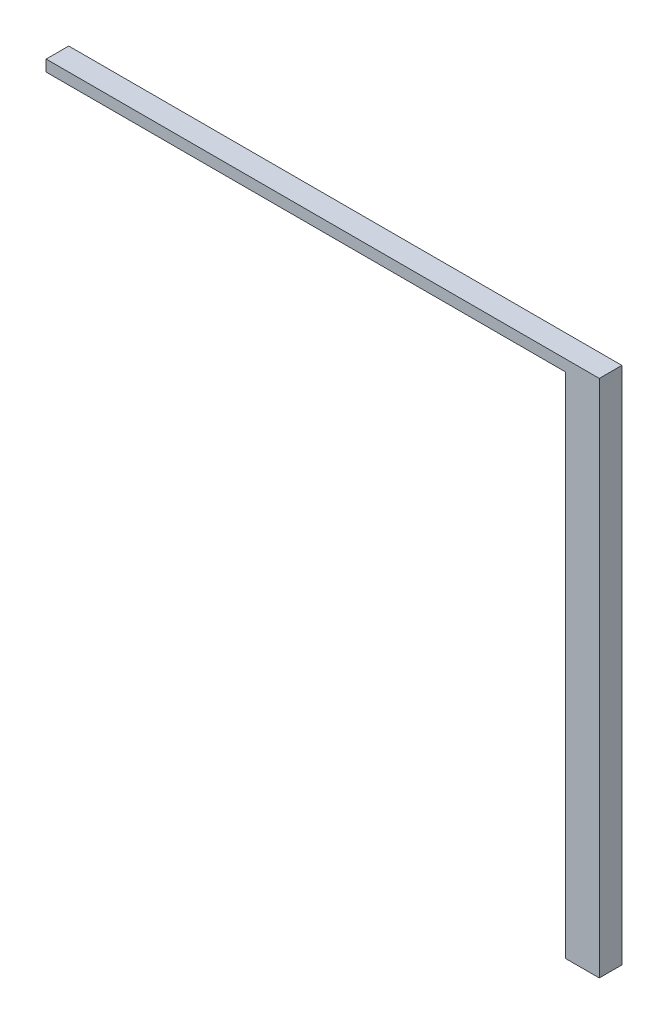
SolidWorks part; units mm, degrees
ref_plane "前视基准面" through (0, 0, 0) normal (0, 0, 1) x (1, 0, 0)
ref_plane "上视基准面" through (0, 0, 0) normal (0, 1, 0) x (1, 0, 0)
ref_plane "右视基准面" through (0, 0, 0) normal (1, 0, 0) x (0, 0, -1)
other "Configuration Table"
sketch "草图1" plane through (0, 0, 0) normal (0, 1, 0) x (1, 0, 0)
  line L1 (0, 0) -> (-30, 0)
  line L2 (0, 0) -> (0, 20)
  line L3 (0, 20) -> (-30, 20)
  line L4 (-30, 0) -> (-30, 20)
  dimension "D1" = 20
  dimension "D2" = 30
extrude "凸台-拉伸1" add sketch "草图1" along normal blind 460
sketch "草图2" plane through (-30, 0, 0) normal (-1, 0, 0) x (0, 0, 1)
  line L0 (-20, 460) -> (-20, 0) construction
  line L1 (0, 460) -> (-20, 460)
  line L2 (0, 460) -> (0, 450)
  line L3 (0, 450) -> (-20, 450)
  line L4 (-20, 460) -> (-20, 450)
  dimension "D1" = 10
extrude "凸台-拉伸2" add sketch "草图2" along normal blind 460
